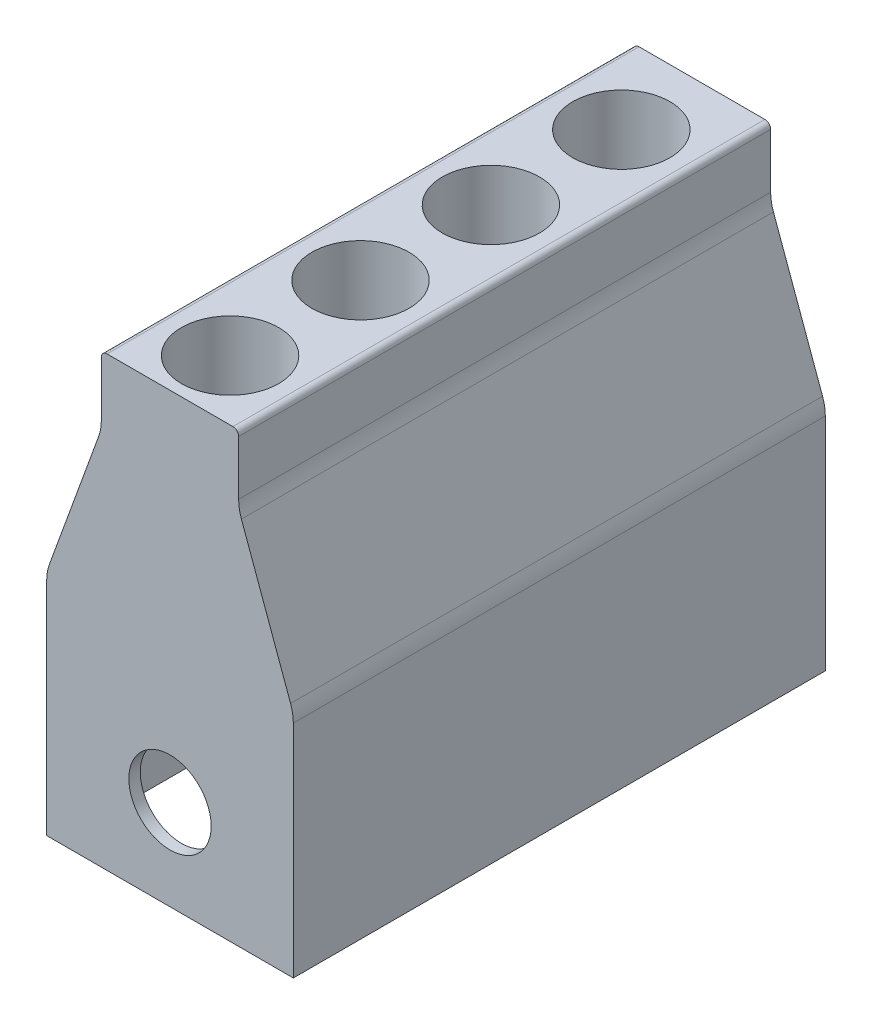
SolidWorks part; units mm, degrees
material "1060 Alloy"
ref_plane "Front Plane" through (0, 0, 0) normal (0, 0, 1) x (1, 0, 0)
ref_plane "Top Plane" through (0, 0, 0) normal (0, 1, 0) x (1, 0, 0)
ref_plane "Right Plane" through (0, 0, 0) normal (1, 0, 0) x (0, 0, -1)
sketch "Sketch1" plane through (0, 0, 0) normal (0, 0, 1) x (1, 0, 0)
  line L0 (107.8023, 0) -> (-107.8023, 0)
  line L1 (-107.8023, 0) -> (-107.8023, 192.9469)
  line L2 (-105.39, 206.6277) -> (-62.4123, 324.708)
  line L3 (-60, 338.3888) -> (-60, 386)
  line L4 (-55, 391) -> (55, 391)
  line L5 (0, 391) -> (0, 0) construction
  line L6 (0, -55) -> (0, 55) construction
  line L7 (60, 338.3888) -> (60, 386)
  line L8 (105.39, 206.6277) -> (62.4123, 324.708)
  line L9 (107.8023, 0) -> (107.8023, 192.9469)
  arc A0 (105.39, 206.6277) -> (107.8023, 192.9469) centre (67.8023, 192.9469) cw
  arc A1 (60, 338.3888) -> (62.4123, 324.708) centre (100, 338.3888) ccw
  arc A2 (-107.8023, 192.9469) -> (-105.39, 206.6277) centre (-67.8023, 192.9469) cw
  arc A3 (-62.4123, 324.708) -> (-60, 338.3888) centre (-100, 338.3888) ccw
  arc A4 (60, 386) -> (55, 391) centre (55, 386) ccw
  arc A5 (-60, 386) -> (-55, 391) centre (-55, 386) cw
  point P15 (107.8023, 200)
  point P18 (60, 331.3358)
  point P21 (-107.8023, 200)
  point P24 (-60, 331.3358)
  point P27 (60, 391)
  point P30 (-60, 391)
  dimension "D6" = 40
  dimension "D7" = 5
  dimension "D1" = 120
  dimension "D2" = 200
  dimension "D3" = 139.7646
  dimension "D4" = 200
  dimension "D5" = 391
extrude "Boss-Extrude1" add sketch "Sketch1" along normal blind 465
shell "Shell1" thickness 10
sketch "Sketch2" plane through (0, 391, 0) normal (0, 1, 0) x (1, 0, 0)
  line L0 (-55, -412.5024) -> (55, -412.5024) construction
  line L2 (-55, -70.5024) -> (55, -70.5024) construction
  line L3 (-55, -184.5024) -> (55, -184.5024) construction
  line L4 (-55, -298.5024) -> (55, -298.5024) construction
  circle A0 centre (0, -70.5024) radius 42.5
  circle A1 centre (0, -184.5024) radius 42.5
  circle A2 centre (0, -298.5024) radius 42.5
  circle A3 centre (0, -412.5024) radius 42.5
  point P8 (0, -28.0024)
  point P9 (0, -142.0024)
  point P10 (0, -113.0024)
  point P11 (0, -370.0024)
  point P12 (0, -256.0024)
  point P13 (0, -455.0024)
  point P14 (0, -341.0024)
  point P16 (0, -227.0024)
  dimension "D1" = 85
sketch "Sketch3" plane through (0, 0, 465) normal (0, 0, 1) x (1, 0, 0)
  circle A0 centre (0, 79) radius 36
  dimension "D1" = 36
  dimension "D2" = 79
extrude "Cut-Extrude2" cut sketch "Sketch3" against normal blind 570
extrude "Cut-Extrude3" cut sketch "Sketch2" against normal blind 10
sketch "Sketch6" plane through (0, 391, 0) normal (0, 1, 0) x (1, 0, 0)
  circle A0 centre (0, -412.5024) radius 42.5 construction
  circle A1 centre (0, -298.5024) radius 42.5 construction
  circle A2 centre (0, -184.5024) radius 42.5 construction
  circle A3 centre (0, -70.5024) radius 42.5 construction
  circle A4 centre (0, -412.5024) radius 42.5
  circle A5 centre (0, -298.5024) radius 42.5
  circle A6 centre (0, -184.5024) radius 42.5
  circle A7 centre (0, -70.5024) radius 42.5
  circle A8 centre (0, -412.5024) radius 45.5
  circle A9 centre (0, -298.5024) radius 45.5
  circle A10 centre (0, -184.5024) radius 45.5
  circle A11 centre (0, -70.5024) radius 45.5
  dimension "D1" = 3
extrude "Boss-Extrude14" add sketch "Sketch6" against normal blind 120
